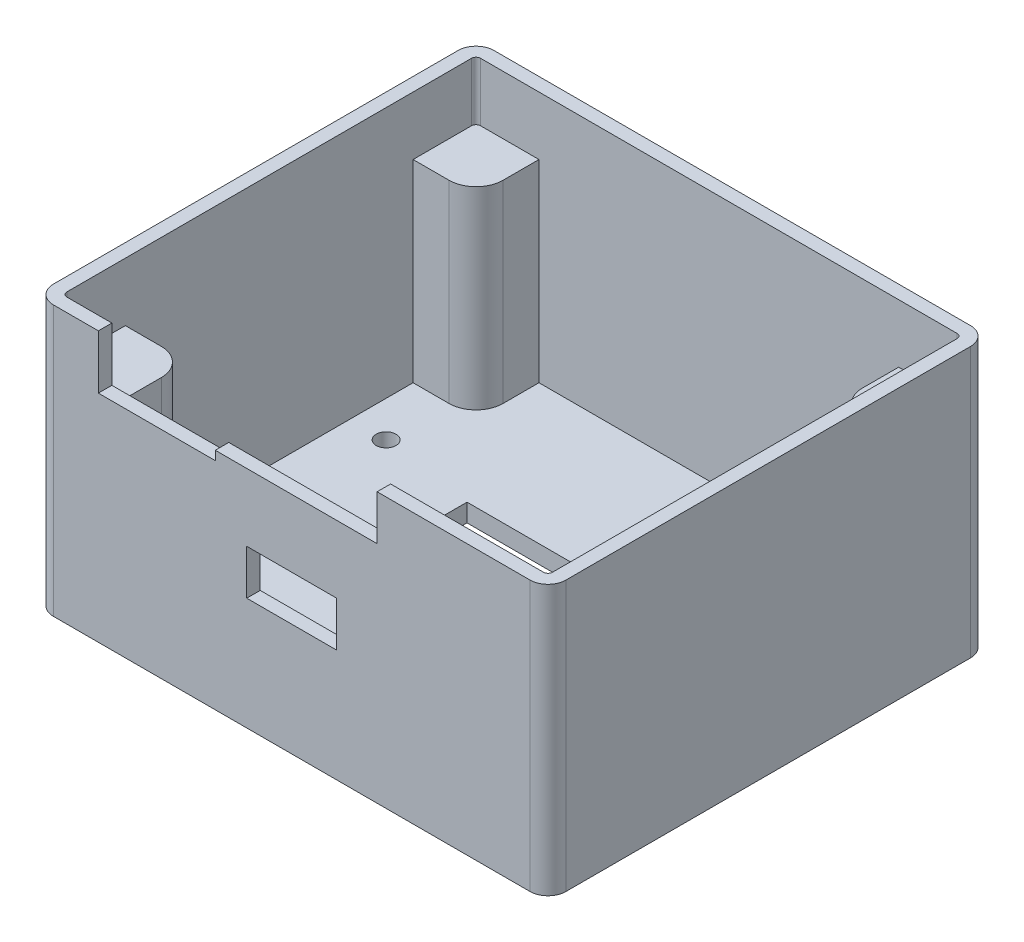
SolidWorks part; units mm, degrees
ref_plane "Front" through (0, 0, 0) normal (0, 0, 1) x (1, 0, 0)
ref_plane "Top" through (0, 0, 0) normal (0, 1, 0) x (1, 0, 0)
ref_plane "Right" through (0, 0, 0) normal (1, 0, 0) x (0, 0, -1)
sketch "草图1" plane through (0, 0, 0) normal (0, 1, 0) x (1, 0, 0)
  line L1 (-26.5, -24.5) -> (26.5, -24.5)
  line L2 (-28.5, -22.5) -> (-28.5, 22.5)
  line L3 (-26.5, 24.5) -> (26.5, 24.5)
  line L4 (28.5, -22.5) -> (28.5, 22.5)
  line L5 (-28.5, -24.5) -> (28.5, 24.5) construction
  line L6 (-28.5, 24.5) -> (28.5, -24.5) construction
  arc A0 (-26.5, -24.5) -> (-28.5, -22.5) centre (-26.5, -22.5) cw
  arc A1 (26.5, -24.5) -> (28.5, -22.5) centre (26.5, -22.5) ccw
  arc A2 (28.5, 22.5) -> (26.5, 24.5) centre (26.5, 22.5) ccw
  arc A3 (-26.5, 24.5) -> (-28.5, 22.5) centre (-26.5, 22.5) ccw
  point P0 (0, 0)
  dimension "D3" = 2
  dimension "D1" = 57
  dimension "D2" = 49
extrude "凸台-拉伸1" add sketch "草图1" along normal blind 30
sketch "草图2" plane through (0, 30, 0) normal (0, 1, 0) x (1, 0, 0)
  line L9 (-26.5, -23) -> (26.5, -23)
  line L10 (27, -22.5) -> (27, 22.5)
  line L11 (26.5, 23) -> (-26.5, 23)
  line L12 (-27, 22.5) -> (-27, -22.5)
  line L13 (-26.5, -23) -> (26.5, -23)
  line L14 (27, -22.5) -> (27, 22.5)
  line L15 (26.5, 23) -> (-26.5, 23)
  line L16 (-27, 22.5) -> (-27, -22.5)
  arc A4 (-27, -22.5) -> (-26.5, -23) centre (-26.5, -22.5) ccw
  arc A5 (-27, -22.5) -> (-26.5, -23) centre (-26.5, -22.5) ccw
  arc A6 (26.5, -23) -> (27, -22.5) centre (26.5, -22.5) ccw
  arc A7 (26.5, -23) -> (27, -22.5) centre (26.5, -22.5) ccw
  arc A8 (27, 22.5) -> (26.5, 23) centre (26.5, 22.5) ccw
  arc A9 (27, 22.5) -> (26.5, 23) centre (26.5, 22.5) ccw
  arc A10 (-26.5, 23) -> (-27, 22.5) centre (-26.5, 22.5) ccw
  arc A11 (-26.5, 23) -> (-27, 22.5) centre (-26.5, 22.5) ccw
  dimension "D1" = 1.5
extrude "切除-拉伸1" cut sketch "草图2" against normal blind 28
sketch "草图3" plane through (0, 2, 0) normal (0, 1, 0) x (1, 0, 0)
  line L0 (-27, 22.5) -> (-27, -22.5) construction
  line L1 (-26.5, -23) -> (26.5, -23) construction
  line L2 (-27, -16) -> (-23, -16)
  line L3 (-20, -19) -> (-20, -23)
  line L4 (-27, 22.5) -> (-27, -22.5) construction
  line L6 (-27, 16) -> (-23, 16)
  line L7 (-20, 19) -> (-20, 23)
  line L8 (26.5, 23) -> (-26.5, 23) construction
  line L11 (20, 23) -> (20, 19)
  line L12 (23, 16) -> (27, 16)
  line L13 (27, -22.5) -> (27, 22.5) construction
  line L14 (27, -22.5) -> (27, 22.5) construction
  line L15 (26.5, 23) -> (-26.5, 23) construction
  line L16 (-20, 23) -> (-26.5, 23)
  line L17 (-27, -16) -> (-27, -22.5)
  line L20 (27, -22.5) -> (27, 22.5)
  line L21 (26.5, 23) -> (-26.5, 23)
  line L22 (-27, 22.5) -> (-27, -22.5)
  line L23 (-26.5, -23) -> (26.5, -23)
  line L24 (27, 16) -> (27, 22.5)
  line L25 (26.5, 23) -> (20, 23)
  line L26 (-27, 22.5) -> (-27, 16)
  line L27 (-26.5, -23) -> (-20, -23)
  circle A0 centre (-23.5, -19.5) radius 1.1 construction
  circle A1 centre (-23.5, 19.5) radius 1.1 construction
  circle A2 centre (23.5, 19.5) radius 1.1 construction
  arc A3 (-20, -19) -> (-23, -16) centre (-23, -19) ccw
  arc A4 (-20, 19) -> (-23, 16) centre (-23, 19) cw
  arc A5 (23, 16) -> (20, 19) centre (23, 19) cw
  arc A10 (26.5, -23) -> (27, -22.5) centre (26.5, -22.5) ccw
  arc A11 (27, 22.5) -> (26.5, 23) centre (26.5, 22.5) ccw
  arc A12 (-26.5, 23) -> (-27, 22.5) centre (-26.5, 22.5) ccw
  arc A13 (-27, -22.5) -> (-26.5, -23) centre (-26.5, -22.5) ccw
  arc A15 (27, 22.5) -> (26.5, 23) centre (26.5, 22.5) ccw
  arc A16 (-26.5, 23) -> (-27, 22.5) centre (-26.5, 22.5) ccw
  arc A17 (-27, -22.5) -> (-26.5, -23) centre (-26.5, -22.5) ccw
  point P17 (-20, -16)
  point P25 (-20, 16)
  dimension "D7" = 2.2
  dimension "D8" = 3
  dimension "D11" = 3
  dimension "D12" = 3
  dimension "D1" = 47
  dimension "D2" = 39
  dimension "D3" = 3.5
  dimension "D4" = 3.5
  dimension "D5" = 7
  dimension "D6" = 7
  dimension "D9" = 7
  dimension "D10" = 7
  dimension "D13" = 7
  dimension "D14" = 7
  dimension "D15" = 0
extrude "凸台-拉伸2" add sketch "草图3" along normal blind 21.5
sketch "草图4" plane through (0, 0, 24.5) normal (0, 0, 1) x (1, 0, 0)
  line L0 (-26.5, 30) -> (26.5, 30) construction
  line L1 (-21.5, 30) -> (9.5, 30)
  line L2 (-21.5, 30) -> (-21.5, 24)
  line L3 (-8.5, 25) -> (9.5, 25)
  line L4 (9.5, 30) -> (9.5, 25)
  line L5 (-28.5, 30) -> (-28.5, 0) construction
  line L6 (-8.5, 25) -> (-8.5, 24)
  line L7 (-8.5, 24) -> (-21.5, 24)
  dimension "D1" = 7
  dimension "D2" = 6
  dimension "D3" = 1
  dimension "D4" = 31
  dimension "D5" = 13
extrude "切除-拉伸2" cut sketch "草图4" against normal blind 1.5
hole_wizard "Ø2.2 (2.2) 直径孔1" positions "草图6" profile "草图5" hole size "Ø2.2" standard "GB" end condition up to next
sketch "草图6" plane through (0, 0, 0) normal (0, -1, 0) x (-1, 0, 0)
  line L0 (23, -9) -> (23, 9) construction
  line L2 (-23, -9) -> (-23, 9) construction
  line L4 (23, 0) -> (0, 0) construction
  line L5 (0, 0) -> (-23, 0) construction
  point P0 (23, -9)
  point P2 (23, 9)
  point P4 (-23, -9)
  point P6 (-23, 9)
  dimension "D1" = 18
  dimension "D2" = 46
sketch "草图5" plane through (-23, 0, 9) normal (1, 0, 0) x (0, 0, -1)
  line L0 (0, 0) -> (0, 2)
  line L1 (0, 2) -> (1.1, 2)
  line L2 (1.1, 2) -> (1.1, 0)
  line L5 (1.1, 0) -> (0, 0)
  line L11 (0, -6.35) -> (0, 107.95) construction
  dimension "通孔孔直径" = 2.2
  dimension "通孔孔深度" = 2
sketch "草图7" plane through (0, 2, 0) normal (0, 1, 0) x (1, 0, 0)
  line L2 (-12.5, -7.5) -> (12.5, -7.5)
  line L3 (-12.5, -7.5) -> (-12.5, 7.5)
  line L4 (-12.5, 7.5) -> (12.5, 7.5)
  line L6 (12.5, -7.5) -> (12.5, 7.5)
  line L7 (-12.5, -7.5) -> (12.5, 7.5) construction
  line L8 (-12.5, 7.5) -> (12.5, -7.5) construction
  point P0 (0, 0)
  dimension "D1" = 25
  dimension "D2" = 15
extrude "切除-拉伸3" cut sketch "草图7" against normal up to next
sketch "草图8" plane through (0, 0, 24.5) normal (0, 0, 1) x (1, 0, 0)
  line L1 (-5, 17.5) -> (5, 17.5)
  line L2 (-5, 17.5) -> (-5, 12.5)
  line L3 (-5, 12.5) -> (5, 12.5)
  line L4 (5, 17.5) -> (5, 12.5)
  line L5 (-5, 17.5) -> (5, 12.5) construction
  line L6 (-5, 12.5) -> (5, 17.5) construction
  point P0 (0, 15)
  dimension "D1" = 5
  dimension "D2" = 10
  dimension "D3" = 15
extrude "切除-拉伸4" cut sketch "草图8" against normal up to next
